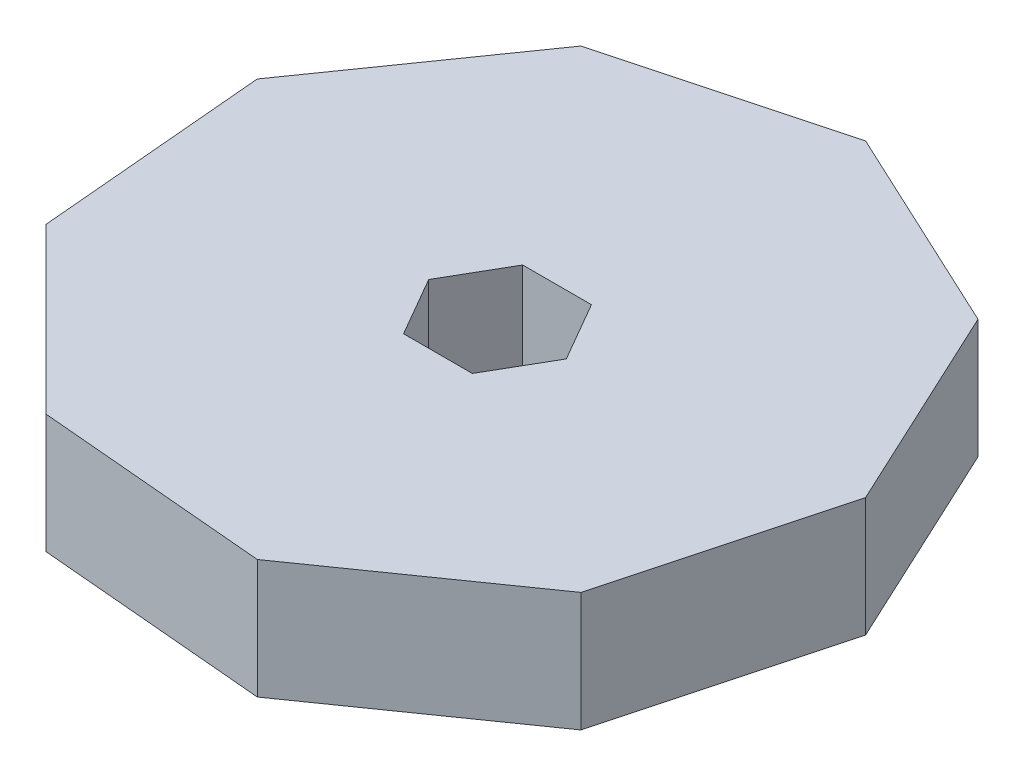
SolidWorks part; units mm, degrees
material "ABS"
ref_plane "Front Plane" through (0, 0, 0) normal (0, 0, 1) x (1, 0, 0)
ref_plane "Top Plane" through (0, 0, 0) normal (0, 1, 0) x (1, 0, 0)
ref_plane "Right Plane" through (0, 0, 0) normal (1, 0, 0) x (0, 0, -1)
sketch "Sketch1" plane through (0, 0, 0) normal (0, 1, 0) x (1, 0, 0)
  line L0 (0, 0) -> (0, 14.1585) construction
  line L7 (14.835, -10.3876) -> (18.0413, 1.5784)
  line L8 (18.0413, 1.5784) -> (12.8058, 12.8058)
  line L9 (12.8058, 12.8058) -> (1.5784, 18.0413)
  line L10 (1.5784, 18.0413) -> (-10.3876, 14.835)
  line L11 (-10.3876, 14.835) -> (-17.4931, 4.6873)
  line L12 (-17.4931, 4.6873) -> (-16.4134, -7.6537)
  line L13 (-16.4134, -7.6537) -> (-7.6537, -16.4134)
  line L14 (-7.6537, -16.4134) -> (4.6873, -17.4931)
  line L15 (4.6873, -17.4931) -> (14.835, -10.3876)
  circle A0 centre (0, 0) radius 17.018 construction
  dimension "D2" = 65
  dimension "D1" = 34.036
extrude "Boss-Extrude1" add sketch "Sketch1" along normal blind 6.35
sketch "Sketch2" plane through (0, 6.35, 0) normal (0, 1, 0) x (1, 0, 0)
  line L1 (1.8331, 3.175) -> (-1.8331, 3.175)
  line L2 (-1.8331, 3.175) -> (-3.6662, 0)
  line L3 (-3.6662, 0) -> (-1.8331, -3.175)
  line L4 (-1.8331, -3.175) -> (1.8331, -3.175)
  line L5 (1.8331, -3.175) -> (3.6662, 0)
  line L6 (3.6662, 0) -> (1.8331, 3.175)
  circle A0 centre (0, 0) radius 3.175 construction
  dimension "D1" = 6.35
extrude "Cut-Extrude1" cut sketch "Sketch2" against normal blind 6.35
